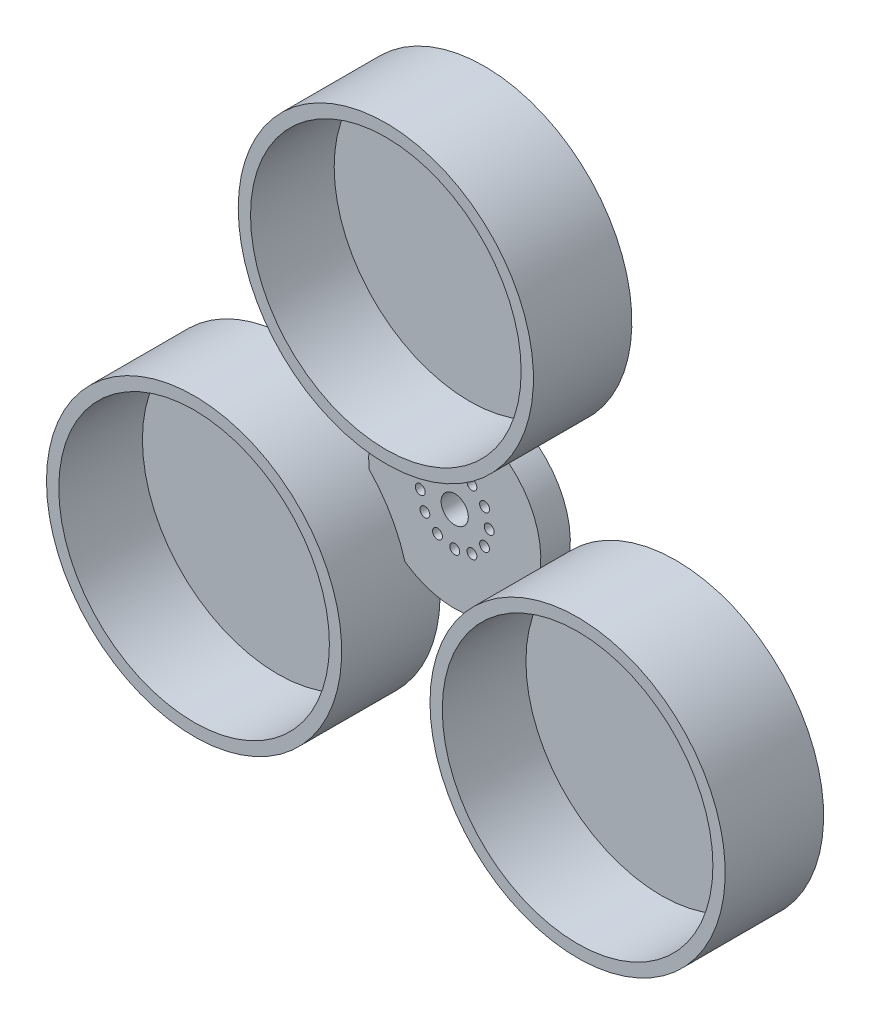
SolidWorks part; units mm, degrees
ref_plane "前视基准面" through (0, 0, 0) normal (0, 0, 1) x (1, 0, 0)
ref_plane "上视基准面" through (0, 0, 0) normal (0, 1, 0) x (1, 0, 0)
ref_plane "右视基准面" through (0, 0, 0) normal (1, 0, 0) x (0, 0, -1)
sketch "草图1" plane through (0, 0, 0) normal (0, 0, 1) x (1, 0, 0)
  circle A0 centre (0, 0) radius 17.5
  circle A1 centre (7, 0) radius 1
  circle A2 centre (6.0622, -3.5) radius 1
  circle A3 centre (3.5, -6.0622) radius 1
  circle A4 centre (0, -7) radius 1
  circle A5 centre (-3.5, -6.0622) radius 1
  circle A6 centre (-6.0622, -3.5) radius 1
  circle A7 centre (-7, 0) radius 1
  circle A8 centre (-6.0622, 3.5) radius 1
  circle A9 centre (-3.5, 6.0622) radius 1
  circle A10 centre (0, 7) radius 1
  circle A11 centre (3.5, 6.0622) radius 1
  circle A12 centre (6.0622, 3.5) radius 1
  circle A13 centre (0, 0) radius 2.76
  point P29 (0, 0)
  dimension "D1" = 35
  dimension "D2" = 2
  dimension "D3" = 7
  dimension "D4" = 12
extrude "凸台-拉伸1" add sketch "草图1" along normal blind 6
sketch "草图2" plane through (0, 0, 0) normal (0, 0, -1) x (-1, 0, 0)
  circle A0 centre (0, 0) radius 5
  dimension "D1" = 10
extrude "切除-拉伸1" cut sketch "草图2" against normal blind 2
sketch "草图4" plane through (0, 0, 0) normal (0, 0, -1) x (-1, 0, 0)
  circle A0 centre (0, 45) radius 30
  circle A1 centre (38.9711, -22.5) radius 30
  circle A2 centre (-38.9711, -22.5) radius 30
  point P9 (0, 0)
  dimension "D1" = 45
  dimension "D2" = 60
  dimension "D3" = 3
extrude "凸台-拉伸2" add sketch "草图4" against normal blind 20
sketch "草图5" plane through (0, 0, 20) normal (0, 0, 1) x (1, 0, 0)
  circle A0 centre (0, 45) radius 27.5
  circle A1 centre (38.9711, -22.5) radius 27.5
  circle A2 centre (-38.9711, -22.5) radius 27.5
  point P9 (0, 0)
  dimension "D1" = 55
  dimension "D2" = 3
extrude "切除-拉伸2" cut sketch "草图5" against normal blind 17
